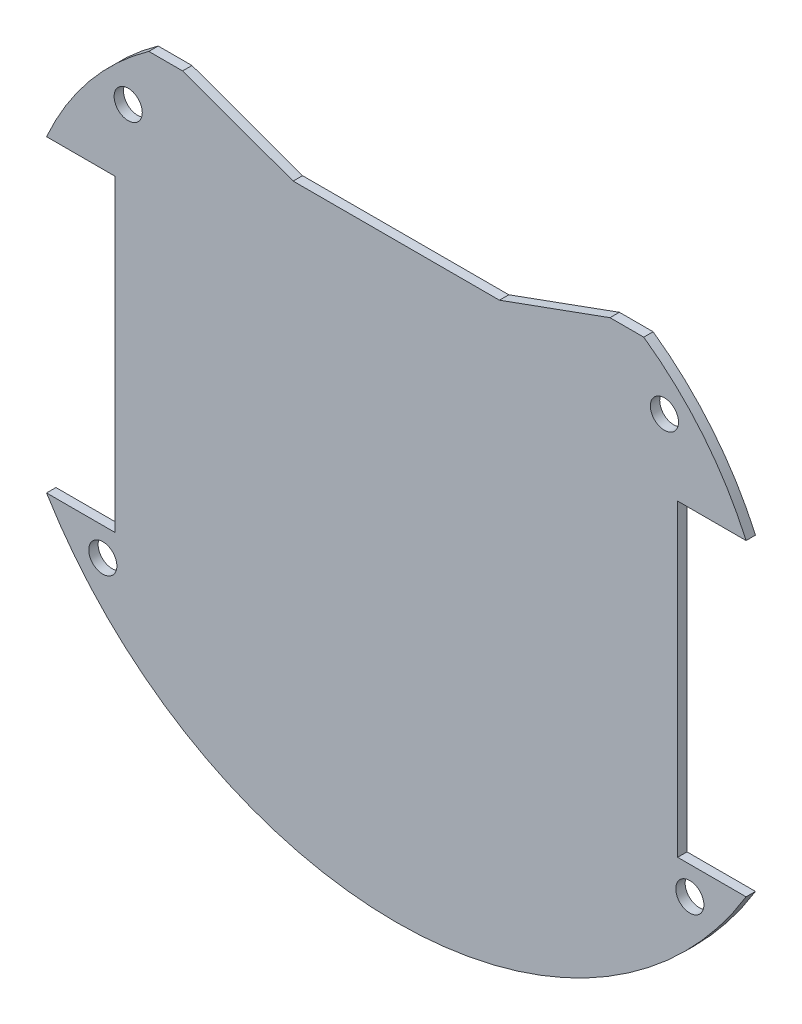
SolidWorks part; units mm, degrees
ref_plane "Front Plane" through (0, 0, 0) normal (0, 0, 1) x (1, 0, 0)
ref_plane "Top Plane" through (0, 0, 0) normal (0, 1, 0) x (1, 0, 0)
ref_plane "Right Plane" through (0, 0, 0) normal (1, 0, 0) x (0, 0, -1)
sketch "Sketch1" plane through (0, 0, 0) normal (0, 0, 1) x (1, 0, 0)
  line L2 (11, 25.5) -> (-11, 25.5)
  line L3 (-11, 25.5) -> (-22.79, 29.7803)
  line L4 (11, 25.5) -> (22.79, 29.7803)
  arc A0 (-22.79, 29.7803) -> (22.79, 29.7803) centre (0, 0) ccw
  arc A1 (-22.79, 29.7803) -> (22.79, 29.7803) centre (0, 0) ccw
  dimension "D2" = 37.5
extrude "Boss-Extrude1" add sketch "Sketch1" along normal blind 3 contours L3 A0 L4 L2
sketch "Sketch2" plane through (0, 0, 3) normal (0, 0, 1) x (1, 0, 0)
  line L0 (0, 0) -> (-25.8, 0) construction
  line L2 (0, 0) -> (0, 15.281) construction
  circle A4 centre (-25.4, 10.4969) radius 1.5
  circle A5 centre (-25.4, -10.4931) radius 1.5
  circle A6 centre (25.4, -10.4931) radius 1.5
  circle A7 centre (25.4, 10.4969) radius 1.5
  point P6 (-25.8, 0)
  dimension "D1" = 25.8
  dimension "D2" = 20.99
extrude "Cut-Extrude3" cut sketch "Sketch2" against normal blind 3
sketch "Sketch3" plane through (0, 0, 3) normal (0, 0, 1) x (1, 0, 0)
  line L1 (-30.76, 21.4493) -> (-30.76, -21.4493)
  line L3 (30.76, 21.4493) -> (30.76, -21.4493)
  arc A0 (-22.79, 29.7803) -> (22.79, 29.7803) centre (0, 0) ccw construction
  arc A1 (-30.76, 21.4493) -> (-30.76, -21.4493) centre (0, 0) ccw
  arc A2 (30.76, 21.4493) -> (30.76, -21.4493) centre (0, 0) cw
  point P10 (-30.76, 0)
extrude "Cut-Extrude4" cut sketch "Sketch3" against normal blind 10
sketch "Sketch4" plane through (0, 0, 3) normal (0, 0, 1) x (1, 0, 0)
  line L0 (-30.76, 21.4493) -> (-30.76, 16.4493) construction
  line L1 (-30.76, -21.4493) -> (-30.76, 21.4493) construction
  line L2 (30.76, 21.4493) -> (30.76, 16.4493) construction
  line L3 (30.76, 21.4493) -> (30.76, -21.4493) construction
  line L4 (-30.76, -21.4493) -> (-30.76, -16.4493) construction
  line L5 (30.76, -21.4493) -> (30.76, -16.4493) construction
  line L6 (-30.76, -16.4493) -> (-33.6997, -16.4493)
  line L7 (-30.76, 16.4493) -> (-33.6997, 16.4493)
  line L8 (30.76, 16.4493) -> (33.6997, 16.4493)
  line L9 (30.76, -16.4493) -> (33.6997, -16.4493)
  line L10 (30.76, -21.4493) -> (30.76, -16.4493)
  line L11 (30.76, 21.4493) -> (30.76, 16.4493)
  line L12 (-30.76, 16.4493) -> (-30.76, 21.4493)
  line L13 (-30.76, -21.4493) -> (-30.76, -16.4493)
  arc A0 (-33.6997, -16.4493) -> (33.6997, -16.4493) centre (0, 0) ccw
  arc A1 (-30.76, 21.4493) -> (-33.6997, 16.4493) centre (0, 0) ccw
  arc A2 (33.6997, 16.4493) -> (30.76, 21.4493) centre (0, 0) ccw
  line M2 (30.76, -21.4493) -> (30.76, 21.4493)
  line M8 (-30.76, 21.4493) -> (-30.76, -21.4493)
  dimension "D1" = 5
  dimension "D2" = 5
extrude "Boss-Extrude2" add sketch "Sketch4" against normal blind 3 contours L6 A0 M8 | A1 L7 M8 | L8 A2 M2 | A0 L9 M2
sketch "Sketch5" plane through (0, 0, 3) normal (0, 0, 1) x (1, 0, 0)
  line L0 (-30.76, 16.4493) -> (-30.2, 16.4493) construction
  line L1 (-30.76, -16.4493) -> (-30.2, -16.4493) construction
  line L2 (0, 0) -> (0, -3.3934) construction
  line L3 (-30.2, -16.4493) -> (-30.76, -16.4493)
  line L4 (-30.2, -16.4493) -> (-30.2, 16.4493)
  line L5 (-30.2, 16.4493) -> (-30.76, 16.4493)
  line L6 (-30.76, -16.4493) -> (-30.76, 16.4493)
  line L7 (30.76, -16.4493) -> (30.2, -16.4493) construction
  line L8 (30.76, 16.4493) -> (30.2, 16.4493) construction
  line L9 (30.76, -16.4493) -> (30.76, 16.4493)
  line L10 (30.2, 16.4493) -> (30.76, 16.4493)
  line L11 (30.2, -16.4493) -> (30.2, 16.4493)
  line L12 (30.2, -16.4493) -> (30.76, -16.4493)
  dimension "D2" = 0.56
extrude "Cut-Extrude5" cut sketch "Sketch5" against normal blind 3
sketch "Sketch6" plane through (0, 0, 3) normal (0, 0, 1) x (1, 0, 0)
  line L1 (-30.2, 16.4493) -> (-30, 16.4493)
  line L2 (-30.2, 16.4493) -> (-30.2, -16.4493)
  line L3 (-30.2, -16.4493) -> (-30, -16.4493)
  line L4 (-30, 16.4493) -> (-30, -16.4493)
  line L5 (30, 16.4493) -> (30, -16.4493)
  line L6 (30.2, -16.4493) -> (30, -16.4493)
  line L7 (30.2, 16.4493) -> (30.2, -16.4493)
  line L8 (30.2, 16.4493) -> (30, 16.4493)
  dimension "D1" = 0.2
extrude "Cut-Extrude6" cut sketch "Sketch6" against normal blind 3
sketch "Sketch7" plane through (0, 0, 3) normal (0, 0, 1) x (1, 0, 0)
  line L0 (0, -37.5) -> (0, -5.6) construction
  line L1 (0, -21.55) -> (-21.15, -21.55) construction
  line L2 (-21.15, -21.55) -> (-19.15, -21.55) construction
  arc A0 (-33.6997, -16.4493) -> (33.6997, -16.4493) centre (0, 0) ccw construction
  circle A1 centre (-19.15, -21.55) radius 2
  circle A2 centre (19.15, -21.55) radius 2
  dimension "D1" = 31.9
  dimension "D2" = 21.15
  dimension "D3" = 2
extrude "Cut-Extrude8" cut sketch "Sketch7" against normal blind 3 contours A1 | A2
sketch "Sketch8" plane through (0, 0, 3) normal (0, 0, 1) x (1, 0, 0)
  line L2 (-33.6997, 16.4493) -> (-37.2997, 16.4493)
  line L3 (33.6997, 16.4493) -> (37.2997, 16.4493)
  line L4 (-22.79, 29.7803) -> (-26.39, 29.7803)
  line L5 (22.79, 29.7803) -> (26.39, 29.7803)
  line L6 (0, 0) -> (0, 7.7073) construction
  arc A0 (-37.2997, 16.4493) -> (-26.39, 29.7803) centre (-7.6125, 3.2837) cw
  arc A1 (37.2997, 16.4493) -> (26.39, 29.7803) centre (7.6125, 3.2837) ccw
  arc A7 (-33.6997, 16.4493) -> (-22.79, 29.7803) centre (0, 0) cw
  arc A8 (22.79, 29.7803) -> (33.6997, 16.4493) centre (0, 0) cw
  dimension "D4" = 3.6
extrude "Boss-Extrude3" add sketch "Sketch8" against normal blind 3
sketch "Sketch9" plane through (0, 0, 3) normal (0, 0, 1) x (1, 0, 0)
  line L0 (0, 0) -> (0, 9.4958) construction
  line L1 (0, -37.5) -> (0, -37.2) construction
  line L2 (4.7339, -37.2) -> (-4.7339, -37.2)
  arc A0 (-33.6997, -16.4493) -> (33.6997, -16.4493) centre (0, 0) ccw construction
  arc A1 (-4.7339, -37.2) -> (4.7339, -37.2) centre (0, 0) ccw
  point P15 (0, -37.2)
  dimension "D1" = 0.3
extrude "Cut-Extrude9" cut sketch "Sketch9" against normal blind 3
sketch "Sketch10" plane through (0, 0, 3) normal (0, 0, 1) x (1, 0, 0)
  line L0 (-33.6997, -16.4493) -> (-37.2997, -16.4493)
  line L1 (-33.6997, -16.4493) -> (-37.2997, -16.4493) construction
  line L2 (0, 0) -> (0, 6.5031) construction
  line L3 (33.6997, -16.4493) -> (37.2997, -16.4493)
  line L4 (-4.7339, -37.2) -> (4.7339, -37.2)
  arc A0 (-37.2997, -16.4493) -> (37.2997, -16.4493) centre (0, 6.1588) ccw
  arc A1 (-33.6997, -16.4493) -> (-4.7339, -37.2) centre (0, 0) ccw
  arc A2 (33.6997, -16.4493) -> (4.7339, -37.2) centre (0, 0) cw
extrude "Boss-Extrude5" add sketch "Sketch10" against normal blind 3
sketch "Sketch11" plane through (0, 0, 3) normal (0, 0, 1) x (1, 0, 0)
  line L0 (-24.59, 29.7803) -> (-24.59, 23.7803) construction
  line L1 (-22.79, 29.7803) -> (-26.39, 29.7803) construction
  line L2 (-24.59, 23.7803) -> (-28.59, 23.7803) construction
  line L3 (0, 25.5) -> (0, 22.2803) construction
  line L4 (11, 25.5) -> (-11, 25.5) construction
  circle A0 centre (-28.59, 23.7803) radius 1.5
  circle A1 centre (28.59, 23.7803) radius 1.5
  dimension "D1" = 6
  dimension "D2" = 4
extrude "Cut-Extrude10" cut sketch "Sketch11" against normal blind 3
sketch "Sketch12" plane through (0, 0, 3) normal (0, 0, 1) x (1, 0, 0)
  line L0 (-19.15, -21.55) -> (-19.15, -28.55) construction
  line L1 (19.15, -21.55) -> (19.15, -28.55) construction
  line L2 (-22.0051, -26.3911) -> (-15.661, -29.3494)
  line L3 (-22.0051, -26.3911) -> (-22.639, -27.7506)
  line L4 (-22.639, -27.7506) -> (-16.2949, -30.7089)
  line L5 (-15.661, -29.3494) -> (-16.2949, -30.7089)
  line L6 (-22.0051, -26.3911) -> (-16.2949, -30.7089) construction
  line L7 (-22.639, -27.7506) -> (-15.661, -29.3494) construction
  line L9 (22.0051, -26.3911) -> (15.661, -29.3494)
  line L10 (22.0051, -26.3911) -> (22.639, -27.7506)
  line L11 (22.639, -27.7506) -> (16.2949, -30.7089)
  line L12 (15.661, -29.3494) -> (16.2949, -30.7089)
  line L13 (22.0051, -26.3911) -> (16.2949, -30.7089) construction
  line L14 (22.639, -27.7506) -> (15.661, -29.3494) construction
  dimension "D1" = 7
  dimension "D2" = 7
  dimension "D3" = 1.5
  dimension "D4" = 7
extrude "Cut-Extrude11" cut sketch "Sketch12" against normal blind 3
sketch "Sketch13" plane through (0, 0, 3) normal (0, 0, 1) x (1, 0, 0)
  line L0 (-25.4, 10.4969) -> (-17.4, 10.4969) construction
  line L1 (-17.4, 10.4969) -> (-17.4, 9.4969) construction
  line L2 (0, 25.5) -> (0, 21.303) construction
  line L3 (-20.9, 10.2469) -> (-13.9, 10.2469)
  line L4 (-20.9, 10.2469) -> (-20.9, 8.7469)
  line L5 (-20.9, 8.7469) -> (-13.9, 8.7469)
  line L6 (-13.9, 10.2469) -> (-13.9, 8.7469)
  line L7 (-20.9, 10.2469) -> (-13.9, 8.7469) construction
  line L8 (-20.9, 8.7469) -> (-13.9, 10.2469) construction
  line L9 (11, 25.5) -> (-11, 25.5) construction
  line L10 (20.9, 8.7469) -> (13.9, 10.2469) construction
  line L11 (20.9, 10.2469) -> (13.9, 8.7469) construction
  line L12 (17.4, 10.4969) -> (17.4, 9.4969) construction
  line L13 (13.9, 10.2469) -> (13.9, 8.7469)
  line L14 (20.9, 8.7469) -> (13.9, 8.7469)
  line L15 (20.9, 10.2469) -> (20.9, 8.7469)
  line L16 (20.9, 10.2469) -> (13.9, 10.2469)
  dimension "D1" = 8
  dimension "D2" = 1
  dimension "D3" = 7
  dimension "D4" = 1.5
extrude "Cut-Extrude12" cut sketch "Sketch13" against normal blind 3
sketch "Sketch14" plane through (0, 0, 3) normal (0, 0, 1) x (1, 0, 0)
  line L0 (-22.0051, -26.3911) -> (-22.639, -27.7506)
  line L1 (-20.9, 10.2469) -> (-13.9, 10.2469)
  line L2 (-20.9, 10.2469) -> (-20.9, 8.7469)
  line L3 (-20.9, 8.7469) -> (-13.9, 8.7469)
  line L4 (-13.9, 10.2469) -> (-13.9, 8.7469)
  line L5 (13.9, 10.2469) -> (20.9, 10.2469)
  line L6 (13.9, 10.2469) -> (13.9, 8.7469)
  line L7 (13.9, 8.7469) -> (20.9, 8.7469)
  line L8 (20.9, 10.2469) -> (20.9, 8.7469)
  line L9 (-22.639, -27.7506) -> (-16.2949, -30.7089)
  line L10 (-16.2949, -30.7089) -> (-15.661, -29.3494)
  line L11 (-15.661, -29.3494) -> (-22.0051, -26.3911)
  line L12 (16.2949, -30.7089) -> (15.661, -29.3494)
  line L13 (15.661, -29.3494) -> (22.0051, -26.3911)
  line L14 (22.0051, -26.3911) -> (22.639, -27.7506)
  line L15 (22.639, -27.7506) -> (16.2949, -30.7089)
  circle A0 centre (-19.15, -21.55) radius 2
  circle A1 centre (19.15, -21.55) radius 2
  circle A2 centre (-25.4, -10.4931) radius 1.5
  circle A3 centre (-25.4, 10.4969) radius 1.5
  circle A4 centre (25.4, 10.4969) radius 1.5
  circle A5 centre (25.4, -10.4931) radius 1.5
extrude "Boss-Extrude6" add sketch "Sketch14" against normal blind 3
sketch "Sketch15" plane through (0, 0, 3) normal (0, 0, 1) x (1, 0, 0)
  line L0 (-37.2997, 16.4493) -> (-30, 16.4493)
  line L1 (-30, 16.4493) -> (-30, -16.4493)
  line L2 (-30, -16.4493) -> (-37.2997, -16.4493)
  line L3 (37.2997, -16.4493) -> (30, -16.4493)
  line L4 (30, -16.4493) -> (30, 16.4493)
  line L5 (30, 16.4493) -> (37.2997, 16.4493)
  line L6 (26.39, 29.7803) -> (22.79, 29.7803)
  line L7 (22.79, 29.7803) -> (11, 25.5)
  line L8 (11, 25.5) -> (-11, 25.5)
  line L9 (-11, 25.5) -> (-22.79, 29.7803)
  line L10 (-22.79, 29.7803) -> (-26.39, 29.7803)
  arc A3 (-37.2997, -16.4493) -> (37.2997, -16.4493) centre (0, 6.1588) ccw
  arc A4 (-37.2997, 16.4493) -> (-26.39, 29.7803) centre (-7.6125, 3.2837) cw
  arc A5 (37.2997, 16.4493) -> (26.39, 29.7803) centre (7.6125, 3.2837) ccw
extrude "Cut-Extrude13" cut sketch "Sketch15" against normal blind 2
sketch "Sketch16" plane through (0, 0, 1) normal (0, 0, 1) x (1, 0, 0)
  line L0 (-37.2997, -16.4493) -> (-31.2997, -16.4493) construction
  line L1 (-30, -16.4493) -> (-37.2997, -16.4493) construction
  line L2 (-31.2997, -16.4493) -> (-31.2997, -19.4493) construction
  line L3 (37.2997, -16.4493) -> (31.2997, -16.4493) construction
  line L4 (37.2997, -16.4493) -> (30, -16.4493) construction
  line L5 (31.2997, -16.4493) -> (31.2997, -19.4493) construction
  circle A0 centre (-31.2997, -19.4493) radius 1.5
  circle A1 centre (31.2997, -19.4493) radius 1.5
  dimension "D3" = 6
  dimension "D1" = 6
  dimension "D2" = 3
extrude "Cut-Extrude14" cut sketch "Sketch16" against normal blind 2
